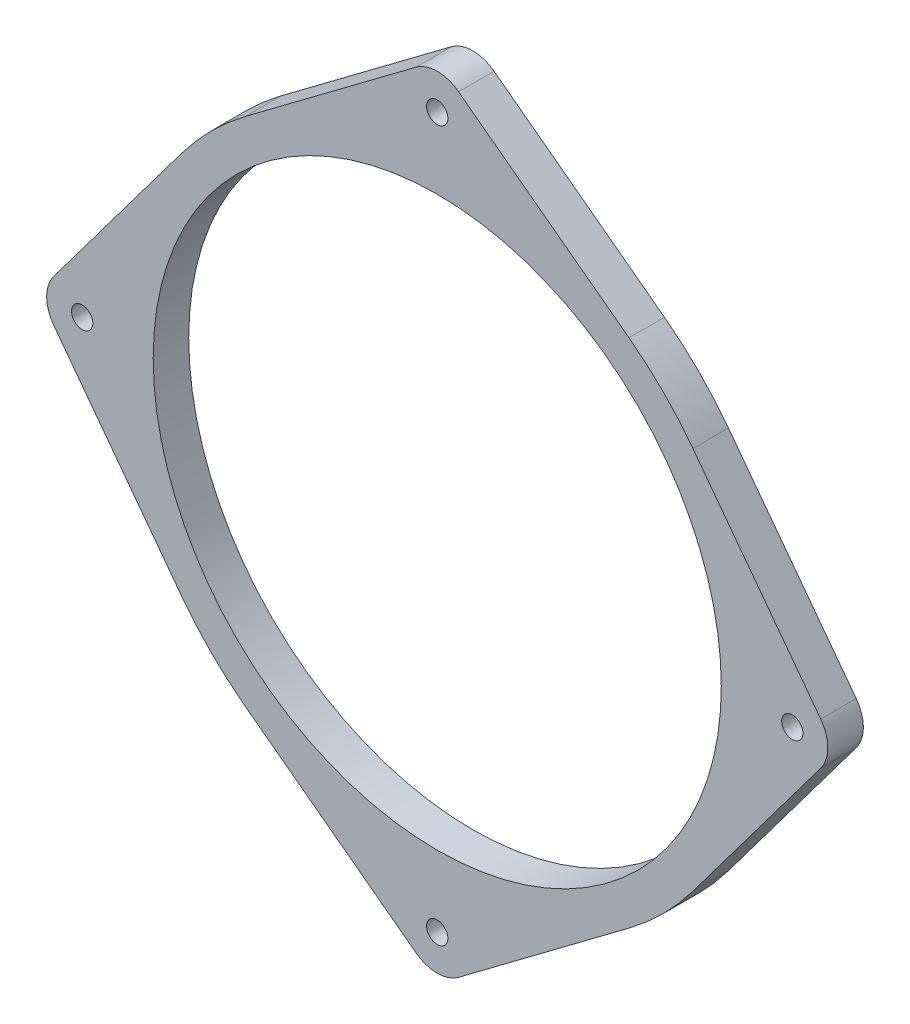
SolidWorks part; units mm, degrees
ref_plane "Plan de face" through (0, 0, 0) normal (0, 0, 1) x (1, 0, 0)
ref_plane "Plan de dessus" through (0, 0, 0) normal (0, 1, 0) x (1, 0, 0)
ref_plane "Plan de droite" through (0, 0, 0) normal (1, 0, 0) x (0, 0, -1)
sketch "Esquisse1" plane through (0, 0, 0) normal (0, 0, 1) x (1, 0, 0)
  line L0 (-89.9976, 0) -> (114.7676, 0) construction
  line L1 (-54, 3) -> (-36, 27)
  line L2 (-54, -3) -> (-36, -27)
  line L3 (3, 54) -> (27, 36)
  line L4 (-3, 54) -> (-27, 36)
  line L5 (54, -3) -> (36, -27)
  line L6 (54, 3) -> (36, 27)
  line L7 (-3, -54) -> (-27, -36)
  line L8 (3, -54) -> (27, -36)
  circle A0 centre (0, 0) radius 40
  circle A1 centre (0, 0) radius 45
  arc A2 (-54, 3) -> (-54, -3) centre (-50, 0) ccw
  circle A3 centre (-50, 0) radius 1.5
  arc A4 (3, 54) -> (-3, 54) centre (0, 50) ccw
  circle A5 centre (0, 50) radius 1.5
  arc A6 (54, -3) -> (54, 3) centre (50, 0) ccw
  circle A7 centre (50, 0) radius 1.5
  arc A8 (-3, -54) -> (3, -54) centre (0, -50) ccw
  circle A9 centre (0, -50) radius 1.5
  point P34 (0, 0)
  dimension "D1" = 80
  dimension "D3" = 10
  dimension "D4" = 3
  dimension "D2" = 5
  dimension "D5" = 4
extrude "Boss.-Extru.2" add sketch "Esquisse1" along normal blind 5 contours A1 L0 A0 | L0 A1 A0 | L3 A4 L4 A1 A5 | L0 A1 L5 A6 A7 | A1 L0 A7 A6 L6 | L7 A8 L8 A1 A9 | A2 L0 A3 A1 L1 | L0 A2 L2 A1 A3
